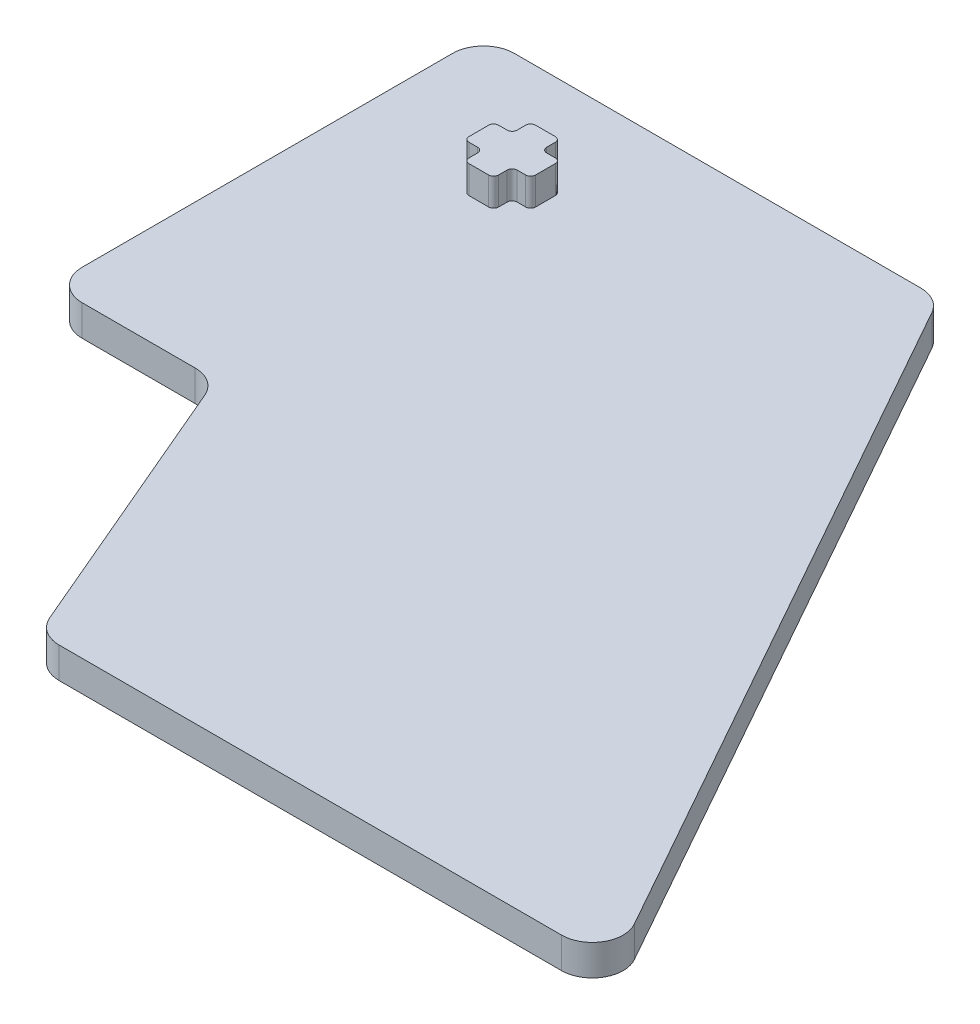
SolidWorks part; units mm, degrees
ref_plane "Front Plane" through (0, 0, 0) normal (0, 0, 1) x (1, 0, 0)
ref_plane "Top Plane" through (0, 0, 0) normal (0, 1, 0) x (1, 0, 0)
ref_plane "Right Plane" through (0, 0, 0) normal (1, 0, 0) x (0, 0, -1)
sketch "Sketch1" plane through (0, 0, 0) normal (0, 1, 0) x (1, 0, 0)
  line L0 (3.175, 44.5079) -> (45.0475, 44.5079)
  line L1 (47.8162, 42.8869) -> (87.0385, -26.992)
  line L2 (84.2699, -31.7211) -> (32.5289, -31.7211)
  line L3 (29.6083, -29.7913) -> (17.7293, -1.9298)
  line L4 (14.8087, 0) -> (3.175, 0)
  line L5 (0, 3.175) -> (0, 41.3329)
  line L27 (13.0298, 30.8763) -> (13.0298, 29.9873)
  line L28 (12.5218, 31.3843) -> (11.6328, 31.3843)
  line L29 (12.5218, 34.4323) -> (11.6328, 34.4323)
  line L30 (13.0298, 34.9403) -> (13.0298, 35.8293)
  line L31 (13.5378, 36.3373) -> (15.5698, 36.3373)
  line L33 (16.0778, 30.8763) -> (16.0778, 29.9873)
  line L34 (16.5858, 31.3843) -> (17.4748, 31.3843)
  line L35 (17.9828, 31.8923) -> (17.9828, 33.9243)
  line L36 (16.5858, 34.4323) -> (17.4748, 34.4323)
  line L37 (16.0778, 34.9403) -> (16.0778, 35.8293)
  line L38 (11.1248, 33.9243) -> (11.1248, 31.8923)
  line L44 (13.5378, 29.4793) -> (15.5698, 29.4793)
  arc A0 (16.5858, 34.4323) -> (16.0778, 34.9403) centre (16.5858, 34.9403) cw
  arc A1 (12.5218, 34.4323) -> (13.0298, 34.9403) centre (12.5218, 34.9403) ccw
  arc A2 (13.0298, 30.8763) -> (12.5218, 31.3843) centre (12.5218, 30.8763) ccw
  arc A3 (16.0778, 30.8763) -> (16.5858, 31.3843) centre (16.5858, 30.8763) cw
  arc A4 (17.4748, 31.3843) -> (17.9828, 31.8923) centre (17.4748, 31.8923) ccw
  arc A5 (17.9828, 33.9243) -> (17.4748, 34.4323) centre (17.4748, 33.9243) ccw
  arc A6 (13.5378, 36.3373) -> (13.0298, 35.8293) centre (13.5378, 35.8293) ccw
  arc A7 (15.5698, 36.3373) -> (16.0778, 35.8293) centre (15.5698, 35.8293) cw
  arc A8 (11.1248, 33.9243) -> (11.6328, 34.4323) centre (11.6328, 33.9243) cw
  arc A9 (11.1248, 31.8923) -> (11.6328, 31.3843) centre (11.6328, 31.8923) ccw
  arc A10 (13.0298, 29.9873) -> (13.5378, 29.4793) centre (13.5378, 29.9873) ccw
  arc A11 (15.5698, 29.4793) -> (16.0778, 29.9873) centre (15.5698, 29.9873) ccw
  arc A12 (45.0475, 44.5079) -> (47.8162, 42.8869) centre (45.0475, 41.3329) cw
  arc A13 (87.0385, -26.992) -> (84.2699, -31.7211) centre (84.2699, -28.5461) cw
  arc A14 (32.5289, -31.7211) -> (29.6083, -29.7913) centre (32.5289, -28.5461) cw
  arc A15 (17.7293, -1.9298) -> (14.8087, 0) centre (14.8087, -3.175) ccw
  arc A16 (3.175, 0) -> (0, 3.175) centre (3.175, 3.175) cw
  arc A17 (3.175, 44.5079) -> (0, 41.3329) centre (3.175, 41.3329) ccw
  point P2 (14.5538, 32.9083)
  point P54 (0, 0)
  dimension "D1" = 0.508
  dimension "D2" = 3.175
extrude "Extrude1" add sketch "Sketch1" against normal blind 3.175
sketch "Sketch4" plane through (0, 0, 0) normal (0, 1, 0) x (1, 0, 0)
  line L0 (15.5698, 36.3373) -> (13.5378, 36.3373) construction
  line L1 (15.5698, 36.3373) -> (13.5378, 36.3373)
  line L2 (16.0778, 34.9403) -> (16.0778, 35.8293) construction
  line L3 (16.0778, 34.9403) -> (16.0778, 35.8293)
  line L4 (17.4748, 34.4323) -> (16.5858, 34.4323) construction
  line L5 (17.4748, 34.4323) -> (16.5858, 34.4323)
  line L6 (17.9828, 31.8923) -> (17.9828, 33.9243) construction
  line L7 (17.9828, 31.8923) -> (17.9828, 33.9243)
  line L8 (16.5858, 31.3843) -> (17.4748, 31.3843) construction
  line L9 (16.5858, 31.3843) -> (17.4748, 31.3843)
  line L10 (16.0778, 29.9873) -> (16.0778, 30.8763) construction
  line L11 (16.0778, 29.9873) -> (16.0778, 30.8763)
  line L12 (13.5378, 29.4793) -> (15.5698, 29.4793) construction
  line L13 (13.5378, 29.4793) -> (15.5698, 29.4793)
  line L14 (13.0298, 30.8763) -> (13.0298, 29.9873) construction
  line L15 (13.0298, 30.8763) -> (13.0298, 29.9873)
  line L16 (11.6328, 31.3843) -> (12.5218, 31.3843) construction
  line L17 (11.6328, 31.3843) -> (12.5218, 31.3843)
  line L18 (11.1248, 33.9243) -> (11.1248, 31.8923) construction
  line L19 (11.1248, 33.9243) -> (11.1248, 31.8923)
  line L20 (12.5218, 34.4323) -> (11.6328, 34.4323) construction
  line L21 (12.5218, 34.4323) -> (11.6328, 34.4323)
  line L22 (13.0298, 35.8293) -> (13.0298, 34.9403) construction
  line L23 (13.0298, 35.8293) -> (13.0298, 34.9403)
  line L24 (17.9828, 32.9083) -> (11.1248, 32.9083) construction
  line L25 (14.5538, 36.3373) -> (14.5538, 29.4793) construction
  arc A0 (16.0778, 35.8293) -> (15.5698, 36.3373) centre (15.5698, 35.8293) ccw construction
  arc A1 (16.0778, 35.8293) -> (15.5698, 36.3373) centre (15.5698, 35.8293) ccw
  arc A2 (16.0778, 34.9403) -> (16.5858, 34.4323) centre (16.5858, 34.9403) ccw construction
  arc A3 (16.0778, 34.9403) -> (16.5858, 34.4323) centre (16.5858, 34.9403) ccw
  arc A4 (17.9828, 33.9243) -> (17.4748, 34.4323) centre (17.4748, 33.9243) ccw construction
  arc A5 (17.9828, 33.9243) -> (17.4748, 34.4323) centre (17.4748, 33.9243) ccw
  arc A6 (17.4748, 31.3843) -> (17.9828, 31.8923) centre (17.4748, 31.8923) ccw construction
  arc A7 (17.4748, 31.3843) -> (17.9828, 31.8923) centre (17.4748, 31.8923) ccw
  arc A8 (16.5858, 31.3843) -> (16.0778, 30.8763) centre (16.5858, 30.8763) ccw construction
  arc A9 (16.5858, 31.3843) -> (16.0778, 30.8763) centre (16.5858, 30.8763) ccw
  arc A10 (15.5698, 29.4793) -> (16.0778, 29.9873) centre (15.5698, 29.9873) ccw construction
  arc A11 (15.5698, 29.4793) -> (16.0778, 29.9873) centre (15.5698, 29.9873) ccw
  arc A12 (13.0298, 29.9873) -> (13.5378, 29.4793) centre (13.5378, 29.9873) ccw construction
  arc A13 (13.0298, 29.9873) -> (13.5378, 29.4793) centre (13.5378, 29.9873) ccw
  arc A14 (13.0298, 30.8763) -> (12.5218, 31.3843) centre (12.5218, 30.8763) ccw construction
  arc A15 (13.0298, 30.8763) -> (12.5218, 31.3843) centre (12.5218, 30.8763) ccw
  arc A16 (11.1248, 31.8923) -> (11.6328, 31.3843) centre (11.6328, 31.8923) ccw construction
  arc A17 (11.1248, 31.8923) -> (11.6328, 31.3843) centre (11.6328, 31.8923) ccw
  arc A18 (11.6328, 34.4323) -> (11.1248, 33.9243) centre (11.6328, 33.9243) ccw construction
  arc A19 (11.6328, 34.4323) -> (11.1248, 33.9243) centre (11.6328, 33.9243) ccw
  arc A20 (12.5218, 34.4323) -> (13.0298, 34.9403) centre (12.5218, 34.9403) ccw construction
  arc A21 (12.5218, 34.4323) -> (13.0298, 34.9403) centre (12.5218, 34.9403) ccw
  arc A22 (13.5378, 36.3373) -> (13.0298, 35.8293) centre (13.5378, 35.8293) ccw construction
  arc A23 (13.5378, 36.3373) -> (13.0298, 35.8293) centre (13.5378, 35.8293) ccw
  point P36 (38.5454, 14.2917)
  point P37 (64.2782, -17.0156)
  point P38 (41.581, -9.2207)
extrude "Extrude2" add sketch "Sketch4" along normal mid plane 5.715
